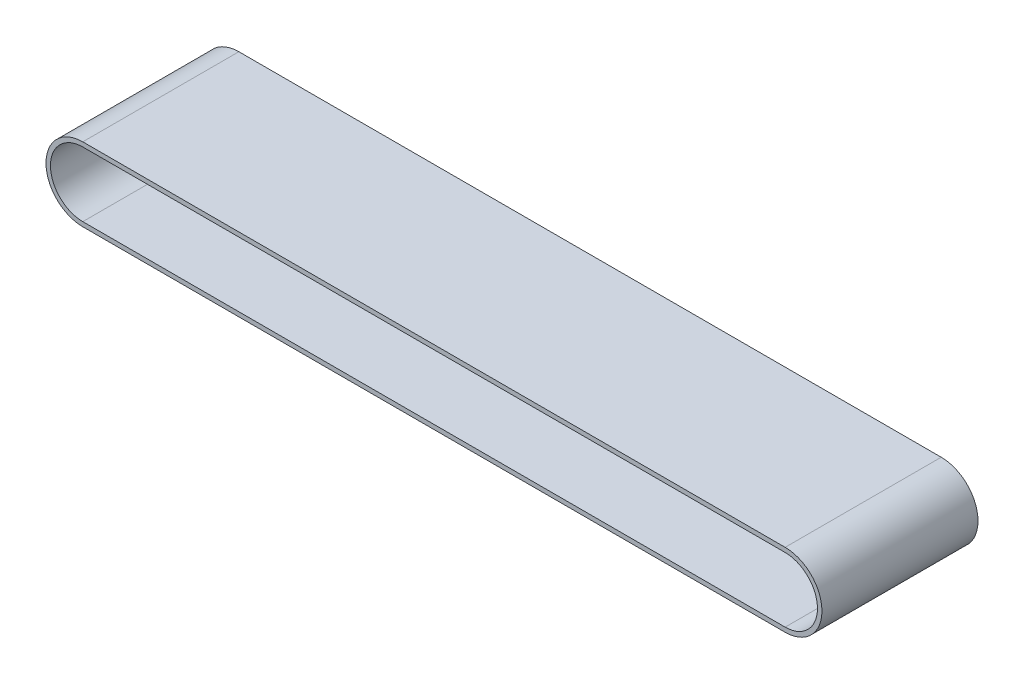
SolidWorks part; units mm, degrees
material "BUTYL"
ref_plane "Alzado" through (0, 0, 0) normal (0, 0, 1) x (1, 0, 0)
ref_plane "Planta" through (0, 0, 0) normal (0, 1, 0) x (1, 0, 0)
ref_plane "Vista lateral" through (0, 0, 0) normal (1, 0, 0) x (0, 0, -1)
sketch "Croquis2" plane through (0, 0, 0) normal (0, 0, 1) x (1, 0, 0)
  line L0 (0, 0) -> (1, 0) construction
  line L1 (0, 0) -> (0, 1) construction
  line L6 (-315, 18.5) -> (0, 18.5)
  line L7 (0, -10.5) -> (-315, -10.5)
  arc A1 (-315, -10.5) -> (-315, 18.5) centre (-315, 4) cw
  arc A3 (0, 18.5) -> (0, -10.5) centre (0, 4) cw
extrude "Extruir-Lámina1" add sketch "Croquis2" along normal mid plane 70 thin thin type one direction wall 2
